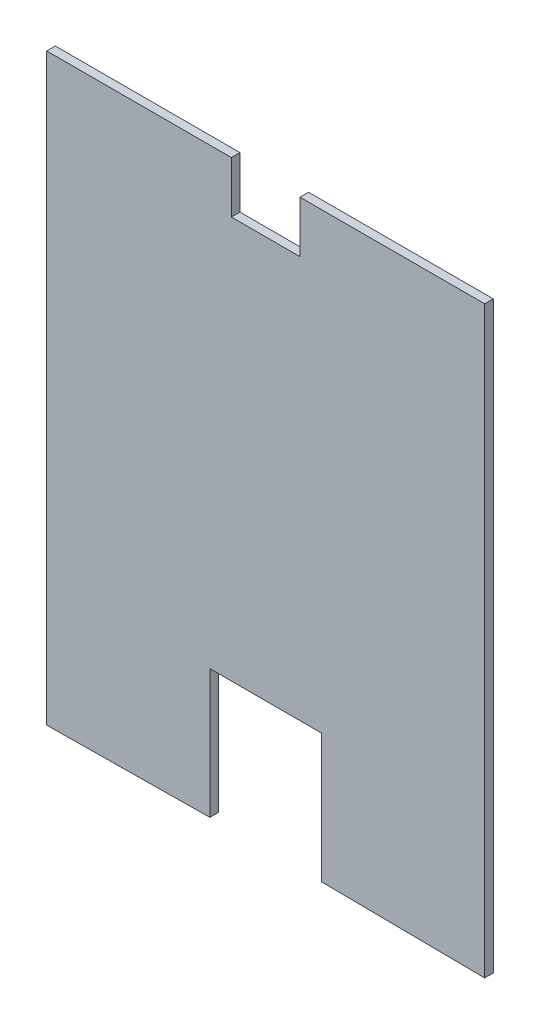
SolidWorks part; units mm, degrees
ref_plane "Front Plane" through (0, 0, 0) normal (0, 0, 1) x (1, 0, 0)
ref_plane "Top Plane" through (0, 0, 0) normal (0, 1, 0) x (1, 0, 0)
ref_plane "Right Plane" through (0, 0, 0) normal (1, 0, 0) x (0, 0, -1)
sketch "Sketch1" plane through (0, 0, 0) normal (0, 0, 1) x (1, 0, 0)
  line L0 (-485.5701, -254.3861) -> (-390.5701, -253.3861)
  line L1 (-485.5701, -254.3861) -> (-230.5701, -254.3861) construction
  line L2 (-485.5701, -254.3861) -> (-485.5701, 85.6139) construction
  line L3 (-485.5701, 85.6139) -> (-230.5701, 85.6139) construction
  line L4 (-230.5701, -254.3861) -> (-230.5701, 85.6139) construction
  line L5 (-390.5701, -253.3861) -> (-325.5701, -253.3861) construction
  line L6 (-390.5701, -253.3861) -> (-390.5701, -178.3861) construction
  line L7 (-390.5701, -178.3861) -> (-325.5701, -178.3861) construction
  line L8 (-325.5701, -253.3861) -> (-325.5701, -178.3861) construction
  line L9 (-390.5701, -253.3861) -> (-390.5701, -178.3861)
  line L10 (-390.5701, -178.3861) -> (-325.5701, -178.3861)
  line L11 (-325.5701, -178.3861) -> (-325.5701, -253.3861)
  line L12 (-325.5701, -253.3861) -> (-230.5701, -254.3861)
  line L13 (-230.5701, -254.3861) -> (-230.5701, 85.6139)
  line L14 (-230.5701, 85.6139) -> (-338.0701, 85.6139)
  line L15 (-358.0701, 85.6139) -> (-338.0701, 85.6139) construction
  line L16 (-358.0701, 85.6139) -> (-358.0701, 55.6139) construction
  line L17 (-358.0701, 55.6139) -> (-338.0701, 55.6139) construction
  line L18 (-338.0701, 85.6139) -> (-338.0701, 55.6139)
  line L19 (-338.0701, 55.6139) -> (-378.0701, 55.6139) construction
  line L20 (-338.0701, 55.6139) -> (-338.0701, 85.6139) construction
  line L21 (-338.0701, 85.6139) -> (-378.0701, 85.6139) construction
  line L22 (-378.0701, 55.6139) -> (-378.0701, 85.6139) construction
  line L23 (-338.0701, 55.6139) -> (-378.0701, 55.6139)
  line L24 (-378.0701, 55.6139) -> (-378.0701, 85.6139)
  line L25 (-378.0701, 85.6139) -> (-485.5701, 85.6139)
  line L26 (-485.5701, 85.6139) -> (-485.5701, -254.3861)
  dimension "D1" = 65
  dimension "D2" = 75
  dimension "D3" = 20
  dimension "D4" = 30
  dimension "D5" = 40
extrude "Boss-Extrude1" add sketch "Sketch1" along normal blind 5
